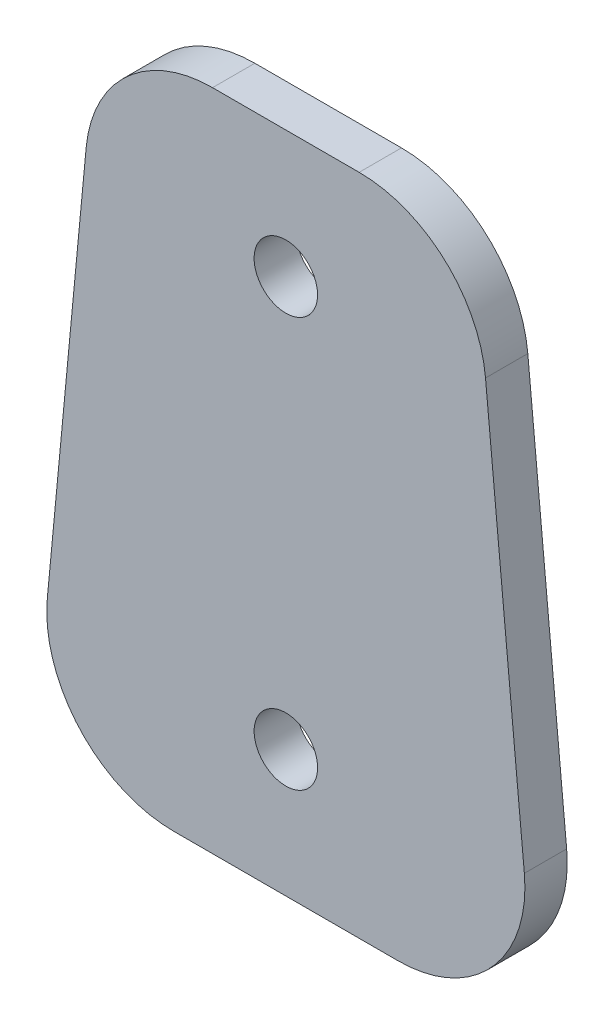
SolidWorks part; units mm, degrees
ref_plane "Front Plane" through (0, 0, 0) normal (0, 0, 1) x (1, 0, 0)
ref_plane "Top Plane" through (0, 0, 0) normal (0, 1, 0) x (1, 0, 0)
ref_plane "Right Plane" through (0, 0, 0) normal (1, 0, 0) x (0, 0, -1)
sketch "Sketch1" plane through (0, 0, 0) normal (0, 0, 1) x (1, 0, 0)
  line L1 (41.7109, 62.3672) -> (38.7964, 93.1012)
  line L3 (8.8286, 93.1012) -> (5.9141, 62.3672)
  line L4 (15.3966, 51.943) -> (32.2284, 51.943)
  line L5 (29.314, 101.727) -> (18.311, 101.727)
  arc A0 (18.311, 101.727) -> (8.8286, 93.1012) centre (18.311, 92.202) ccw
  circle A1 centre (23.8125, 61.468) radius 2.3813
  circle A2 centre (23.8125, 92.202) radius 2.3813
  arc A3 (29.314, 101.727) -> (38.7964, 93.1012) centre (29.314, 92.202) cw
  arc A4 (32.2284, 51.943) -> (41.7109, 62.3672) centre (32.2284, 61.468) ccw
  arc A5 (15.3966, 51.943) -> (5.9141, 62.3672) centre (15.3966, 61.468) cw
  dimension "D7" = 4.7625
  dimension "D8" = 4.7625
  dimension "D2" = 9.525
  dimension "D4" = 30.734
  dimension "D9" = 9.525
  dimension "D10" = 9.525
extrude "Boss-Extrude1" add sketch "Sketch1" along normal blind 3.175
